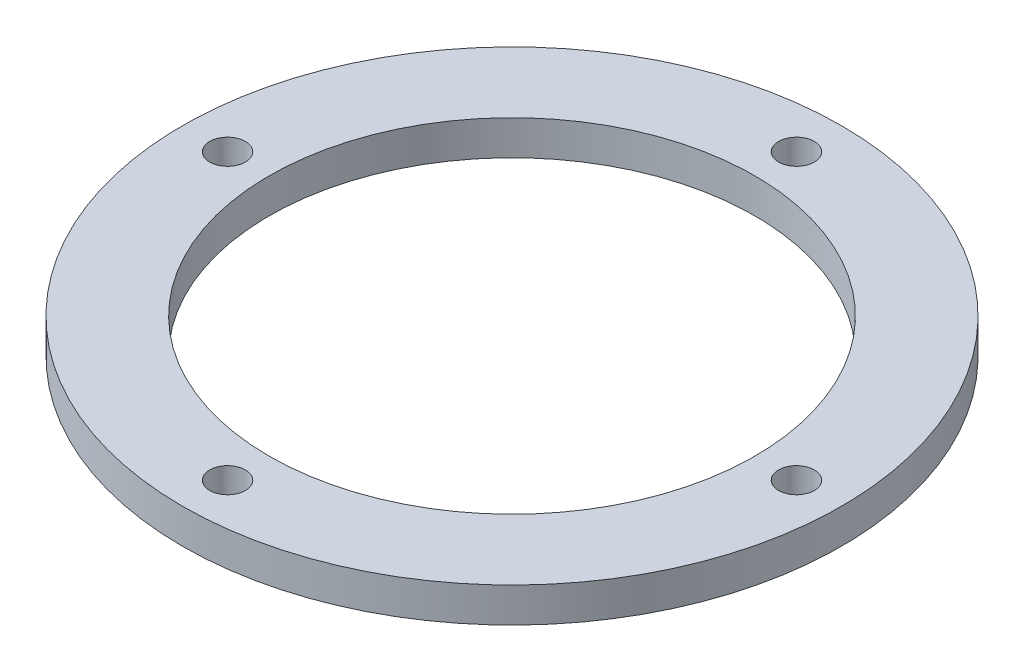
SolidWorks part; units mm, degrees
ref_plane "前视基准面" through (0, 0, 0) normal (0, 0, 1) x (1, 0, 0)
ref_plane "上视基准面" through (0, 0, 0) normal (0, 1, 0) x (1, 0, 0)
ref_plane "右视基准面" through (0, 0, 0) normal (1, 0, 0) x (0, 0, -1)
other "Configuration Table"
sketch "草图1" plane through (0, 0, 0) normal (0, 1, 0) x (1, 0, 0)
  circle A0 centre (0, 0) radius 47.5
  circle A1 centre (0, 0) radius 35
  dimension "D1" = 95
  dimension "D2" = 70
extrude "凸台-拉伸1" add sketch "草图1" along normal blind 5
sketch "草图2" plane through (0, 5, 0) normal (0, 1, 0) x (1, 0, 0)
  line L0 (0, 41) -> (0, 0) construction
  circle A0 centre (0, 41) radius 2.575
  circle A1 centre (41, 0) radius 2.575
  circle A2 centre (0, -41) radius 2.575
  circle A3 centre (-41, 0) radius 2.575
  point P4 (0, 0)
  point P5 (41, 0)
  point P13 (0, 0)
  dimension "D2" = 5.15
  dimension "D1" = 41
  dimension "D3" = 4
extrude "切除-拉伸1" cut sketch "草图2" against normal up to next
